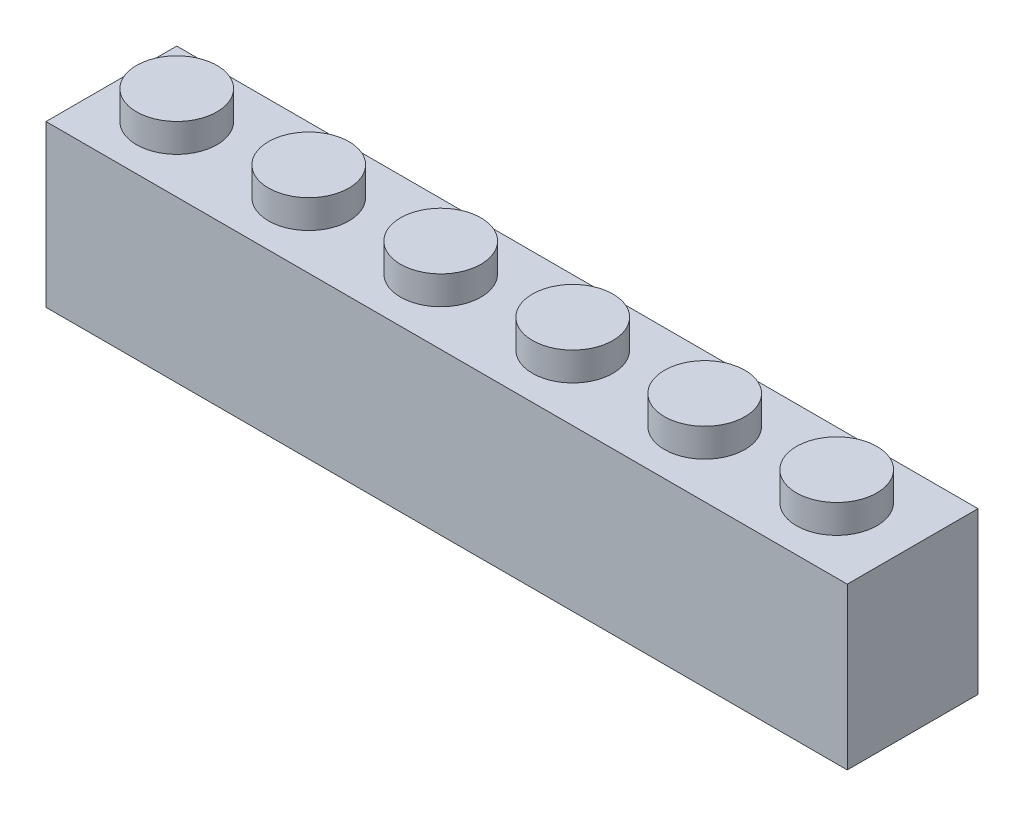
SolidWorks part; units mm, degrees
ref_plane "Спереди" through (0, 0, 0) normal (0, 0, 1) x (1, 0, 0)
ref_plane "Сверху" through (0, 0, 0) normal (0, 1, 0) x (1, 0, 0)
ref_plane "Справа" through (0, 0, 0) normal (1, 0, 0) x (0, 0, -1)
sketch "Эскиз1" plane through (0, 0, 0) normal (0, 1, 0) x (1, 0, 0)
  line L1 (23.9, -3.9) -> (-23.9, -3.9)
  line L2 (23.9, -3.9) -> (23.9, 3.9)
  line L3 (23.9, 3.9) -> (-23.9, 3.9)
  line L4 (-23.9, -3.9) -> (-23.9, 3.9)
  line L5 (23.9, -3.9) -> (-23.9, 3.9) construction
  line L6 (23.9, 3.9) -> (-23.9, -3.9) construction
  point P0 (0, 0)
  dimension "D1" = 47.8
  dimension "D2" = 7.8
extrude "Бобышка-Вытянуть1" add sketch "Эскиз1" along normal blind 9.6
sketch "Эскиз2" plane through (0, 9.6, 0) normal (0, 1, 0) x (1, 0, 0)
  line L0 (-23.9, 3.9) -> (-23.9, -3.9) construction
  line L1 (-23.9, -3.9) -> (23.9, -3.9) construction
  circle A0 centre (-20, 0) radius 2.4
  circle A1 centre (-12.126, 0) radius 2.4
  circle A2 centre (-4.252, 0) radius 2.4
  circle A3 centre (3.622, 0) radius 2.4
  circle A4 centre (11.496, 0) radius 2.4
  circle A5 centre (19.37, 0) radius 2.4
  dimension "D1" = 3.9
  dimension "D2" = 3.9
  dimension "D3" = 6
extrude "Бобышка-Вытянуть2" add sketch "Эскиз2" along normal blind 1.7
sketch "Эскиз3" plane through (0, 0, 0) normal (0, -1, 0) x (1, 0, 0)
  line L0 (-23.9, 3.9) -> (23.9, 3.9) construction
  line L1 (-23.9, -3.9) -> (-23.9, 3.9) construction
  circle A0 centre (-20, 0) radius 2.5
  circle A1 centre (-12.126, 0) radius 2.5
  circle A2 centre (-4.252, 0) radius 2.5
  circle A3 centre (3.622, 0) radius 2.5
  circle A4 centre (11.496, 0) radius 2.5
  circle A5 centre (19.37, 0) radius 2.5
  dimension "D1" = 3.9
  dimension "D3" = 6
  dimension "D2" = 3.9
extrude "Вырез-Вытянуть1" cut sketch "Эскиз3" against normal blind 1.8
